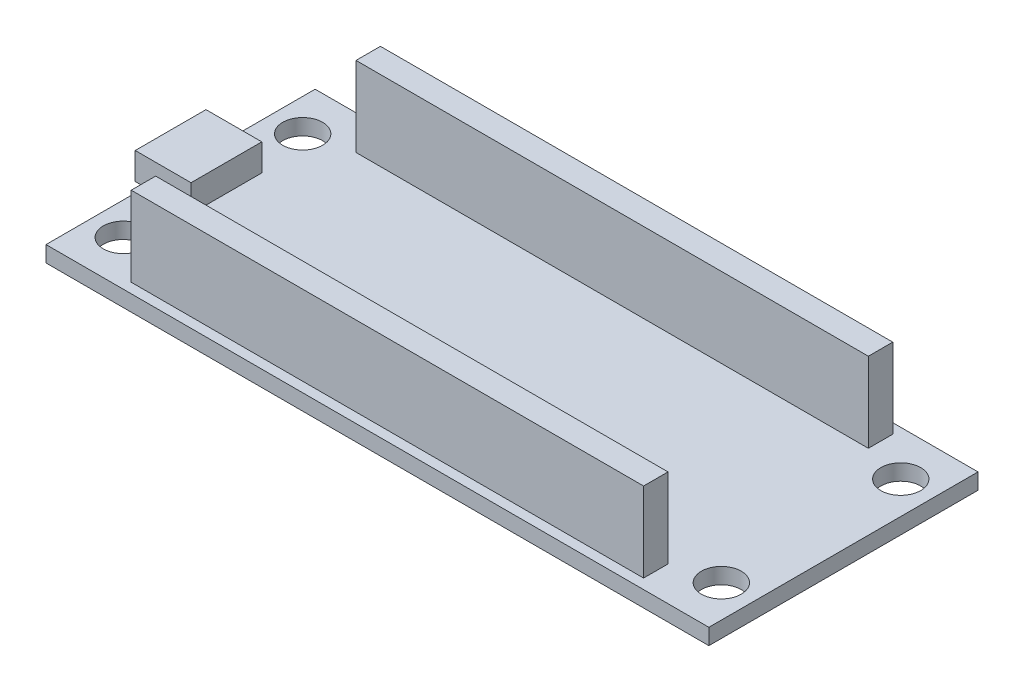
SolidWorks part; units mm, degrees
ref_plane "Front Plane" through (0, 0, 0) normal (0, 0, 1) x (1, 0, 0)
ref_plane "Top Plane" through (0, 0, 0) normal (0, 1, 0) x (1, 0, 0)
ref_plane "Right Plane" through (0, 0, 0) normal (1, 0, 0) x (0, 0, -1)
sketch "Sketch1" plane through (0, 0, 0) normal (0, 1, 0) x (1, 0, 0)
  line L0 (-30, 9) -> (30, 9) construction
  line L1 (-33.25, 13.5) -> (33.25, 13.5)
  line L2 (-33.25, 13.5) -> (-33.25, -13.5)
  line L3 (-33.25, -13.5) -> (33.25, -13.5)
  line L4 (33.25, 13.5) -> (33.25, -13.5)
  line L5 (-33.25, 13.5) -> (33.25, -13.5) construction
  line L6 (-33.25, -13.5) -> (33.25, 13.5) construction
  line L7 (-30, 9) -> (-30, -9) construction
  circle A0 centre (-30, 9) radius 2
  circle A1 centre (-30, -9) radius 2
  circle A2 centre (30, -9) radius 2
  circle A3 centre (30, 9) radius 2
  point P0 (0, 0)
  point P14 (0, 9)
  point P15 (-30, 0)
  point P16 (-33.25, 0)
  dimension "D3" = 4
  dimension "D1" = 66.5
  dimension "D2" = 27
  dimension "D4" = 60
  dimension "D5" = 18
extrude "Boss-Extrude1" add sketch "Sketch1" along normal blind 1.6
sketch "Sketch2" plane through (0, 1.6, 0) normal (0, 1, 0) x (1, 0, 0)
  line L1 (-34.25, 3.55) -> (-28.65, 3.55)
  line L2 (-34.25, 3.55) -> (-34.25, -3.55)
  line L3 (-34.25, -3.55) -> (-28.65, -3.55)
  line L4 (-28.65, 3.55) -> (-28.65, -3.55)
  line L5 (-33.25, 13.5) -> (-33.25, -13.5) construction
  point P6 (-28.65, 0)
  dimension "D1" = 7.1
  dimension "D2" = 5.6
  dimension "D3" = 1
extrude "Boss-Extrude2" add sketch "Sketch2" along normal blind 2.7
sketch "Sketch3" plane through (0, 1.6, 0) normal (0, 1, 0) x (1, 0, 0)
  line L0 (33.25, 13.5) -> (-33.25, 13.5) construction
  line L1 (-25.7, 12.5) -> (25.7, 12.5)
  line L2 (-25.7, 12.5) -> (-25.7, 10.05)
  line L3 (-25.7, 10.05) -> (25.7, 10.05)
  line L4 (25.7, 12.5) -> (25.7, 10.05)
  line L5 (-2.365, 0) -> (2.365, 0) construction
  line L6 (-25.7, -10.05) -> (25.7, -10.05)
  line L7 (25.7, -12.5) -> (25.7, -10.05)
  line L8 (-25.7, -12.5) -> (25.7, -12.5)
  line L9 (-25.7, -12.5) -> (-25.7, -10.05)
  point P4 (0, 10.05)
  dimension "D1" = 1
  dimension "D2" = 2.45
  dimension "D3" = 51.4
extrude "Boss-Extrude3" add sketch "Sketch3" along normal blind 8
